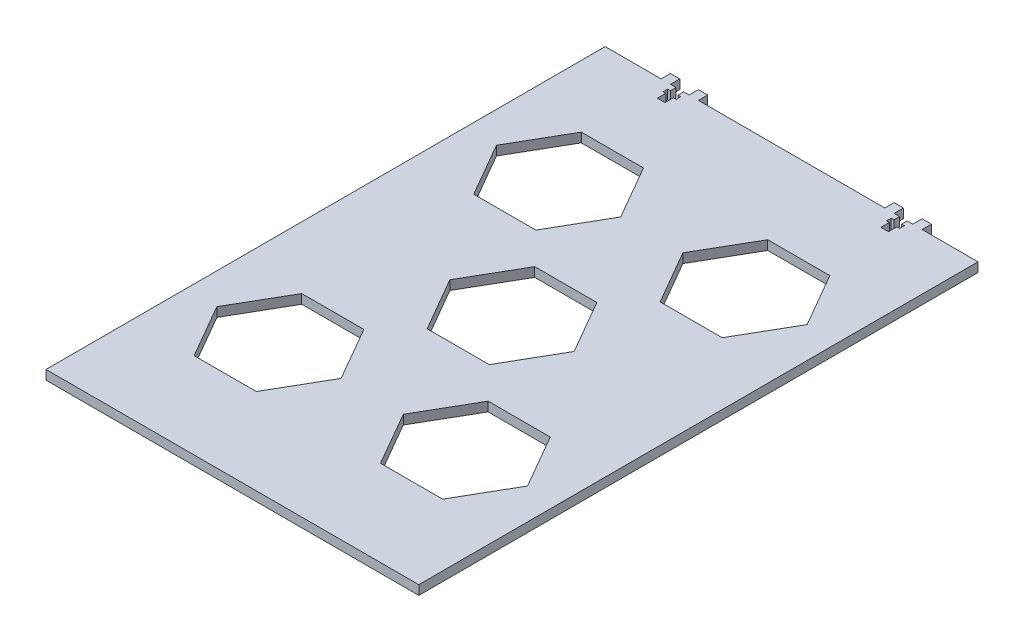
SolidWorks part; units mm, degrees
ref_plane "Front Plane" through (0, 0, 0) normal (0, 0, 1) x (1, 0, 0)
ref_plane "Top Plane" through (0, 0, 0) normal (0, 1, 0) x (1, 0, 0)
ref_plane "Right Plane" through (0, 0, 0) normal (1, 0, 0) x (0, 0, -1)
sketch "Sketch1" plane through (0, 0, 0) normal (0, 1, 0) x (1, 0, 0)
  line L0 (-63.0001, 189.8028) -> (-63.0001, -110.1972) construction
  line L1 (-163.0001, 189.8028) -> (-133.0001, 189.8028)
  line L2 (-163.0001, 189.8028) -> (-163.0001, -110.1972)
  line L3 (-163.0001, -110.1972) -> (36.9999, -110.1972)
  line L4 (36.9999, 189.8028) -> (36.9999, -110.1972)
  line L5 (-122.9649, 179.8028) -> (-122.9649, 208.5217) construction
  line L7 (-113.0001, 189.8028) -> (-113.0001, 194.8028)
  line L8 (-113.0001, 194.8028) -> (-118.0001, 194.8028)
  line L9 (-118.0001, 189.8028) -> (-118.0001, 194.8028)
  line L11 (-128.0001, 189.8028) -> (-128.0001, 194.8028)
  line L12 (-128.0001, 194.8028) -> (-133.0001, 194.8028)
  line L13 (-133.0001, 189.8028) -> (-133.0001, 194.8028)
  line L15 (-125.0001, 189.8028) -> (-125.0001, 186.8028)
  line L16 (-125.0001, 179.8028) -> (-120.9298, 179.8028)
  line L17 (-120.9298, 189.8028) -> (-120.9298, 186.8028)
  line L18 (-125.0001, 186.8028) -> (-126.5001, 186.8028)
  line L20 (-125.0001, 184.3028) -> (-126.5001, 184.3028)
  line L21 (-126.5001, 186.8028) -> (-126.5001, 184.3028)
  line L22 (-120.9298, 184.3028) -> (-119.4298, 184.3028)
  line L23 (-119.4298, 186.8028) -> (-119.4298, 184.3028)
  line L24 (-120.9298, 186.8028) -> (-119.4298, 186.8028)
  line L25 (-125.0001, 184.3028) -> (-125.0001, 179.8028)
  line L26 (-120.9298, 184.3028) -> (-120.9298, 179.8028)
  line L27 (-120.9298, 189.8028) -> (-118.0001, 189.8028)
  line L28 (-128.0001, 189.8028) -> (-125.0001, 189.8028)
  line L29 (-113.0001, 189.8028) -> (-13.0001, 189.8028)
  line L30 (-13.0001, 189.8028) -> (-13.0001, 194.8028)
  line L31 (-13.0001, 194.8028) -> (-8.0001, 194.8028)
  line L32 (-8.0001, 189.8028) -> (-8.0001, 194.8028)
  line L33 (-5.0705, 189.8028) -> (-5.0705, 186.8028)
  line L34 (-5.0705, 186.8028) -> (-6.5705, 186.8028)
  line L35 (-6.5705, 186.8028) -> (-6.5705, 184.3028)
  line L36 (-5.0705, 184.3028) -> (-6.5705, 184.3028)
  line L37 (-5.0705, 184.3028) -> (-5.0705, 179.8028)
  line L38 (-1.0001, 179.8028) -> (-5.0705, 179.8028)
  line L39 (-1.0001, 184.3028) -> (-1.0001, 179.8028)
  line L40 (-1.0001, 184.3028) -> (0.4999, 184.3028)
  line L41 (0.4999, 186.8028) -> (0.4999, 184.3028)
  line L42 (-1.0001, 186.8028) -> (0.4999, 186.8028)
  line L43 (-1.0001, 189.8028) -> (-1.0001, 186.8028)
  line L44 (1.9999, 189.8028) -> (1.9999, 194.8028)
  line L45 (1.9999, 194.8028) -> (6.9999, 194.8028)
  line L46 (6.9999, 189.8028) -> (6.9999, 194.8028)
  line L47 (-8.0001, 189.8028) -> (-5.0705, 189.8028)
  line L48 (6.9999, 189.8028) -> (36.9999, 189.8028)
  line L49 (-1.0001, 189.8028) -> (1.9999, 189.8028)
  point P28 (-128.0001, 192.3028)
  dimension "D1" = 200
  dimension "D2" = 300
  dimension "D3" = 5
  dimension "D4" = 10
  dimension "D5" = 50
  dimension "D6" = 3
  dimension "D7" = 10
  dimension "D8" = 3
  dimension "D9" = 2.5
  dimension "D10" = 1.5
extrude "Boss-Extrude1" add sketch "Sketch1" along normal blind 5
sketch "Sketch2" plane through (0, 5, 0) normal (0, 1, 0) x (1, 0, 0)
  line L0 (-63.0001, 189.8028) -> (-63.0001, -110.1972) construction
  line L1 (-13.0001, 189.8028) -> (-113.0001, 189.8028) construction
  line L2 (-163.0001, -110.1972) -> (36.9999, -110.1972) construction
  line L3 (36.9999, 39.8028) -> (-163.0001, 39.8028) construction
  line L4 (36.9999, -110.1972) -> (36.9999, 189.8028) construction
  line L5 (-163.0001, 189.8028) -> (-163.0001, -110.1972) construction
  line L6 (-163.0001, 189.8028) -> (-63.0001, 39.8028) construction
  line L7 (-63.0001, 189.8028) -> (-163.0001, 39.8028) construction
  line L8 (3.6649, 143.6674) -> (20.3299, 114.8028)
  line L9 (-79.6701, 114.8028) -> (-96.3351, 143.6674)
  line L10 (-96.3351, 143.6674) -> (-129.6651, 143.6674)
  line L11 (-129.6651, 143.6674) -> (-146.3301, 114.8028)
  line L12 (-146.3301, 114.8028) -> (-129.6651, 85.9382)
  line L13 (-129.6651, 85.9382) -> (-96.3351, 85.9382)
  line L14 (-96.3351, 85.9382) -> (-79.6701, 114.8028)
  line L15 (20.3299, 114.8028) -> (3.6649, 85.9382)
  line L16 (3.6649, 85.9382) -> (-29.6651, 85.9382)
  line L17 (-29.6651, 85.9382) -> (-46.3301, 114.8028)
  line L18 (-46.3301, 114.8028) -> (-29.6651, 143.6674)
  line L19 (-29.6651, 143.6674) -> (3.6649, 143.6674)
  line L20 (-29.6651, -64.0618) -> (3.6649, -64.0618)
  line L21 (-46.3301, -35.1972) -> (-29.6651, -64.0618)
  line L22 (-29.6651, -6.3326) -> (-46.3301, -35.1972)
  line L23 (3.6649, -6.3326) -> (-29.6651, -6.3326)
  line L24 (20.3299, -35.1972) -> (3.6649, -6.3326)
  line L25 (3.6649, -64.0618) -> (20.3299, -35.1972)
  line L26 (-79.6701, -35.1972) -> (-96.3351, -64.0618)
  line L27 (-96.3351, -6.3326) -> (-79.6701, -35.1972)
  line L28 (-129.6651, -6.3326) -> (-96.3351, -6.3326)
  line L29 (-146.3301, -35.1972) -> (-129.6651, -6.3326)
  line L30 (-129.6651, -64.0618) -> (-146.3301, -35.1972)
  line L31 (-96.3351, -64.0618) -> (-129.6651, -64.0618)
  line L33 (-29.6701, 39.8028) -> (-46.3351, 68.6674)
  line L34 (-46.3351, 68.6674) -> (-79.6651, 68.6674)
  line L35 (-79.6651, 68.6674) -> (-96.3301, 39.8028)
  line L36 (-96.3301, 39.8028) -> (-79.6651, 10.9382)
  line L37 (-79.6651, 10.9382) -> (-46.3351, 10.9382)
  line L38 (-46.3351, 10.9382) -> (-29.6701, 39.8028)
  circle A0 centre (-113.0001, 114.8028) radius 28.8646 construction
  circle A1 centre (-63.0001, 39.8028) radius 28.8646 construction
  dimension "D1" = 33.33
  dimension "D2" = 33.33
extrude "Cut-Extrude1" cut sketch "Sketch2" against normal blind 5
